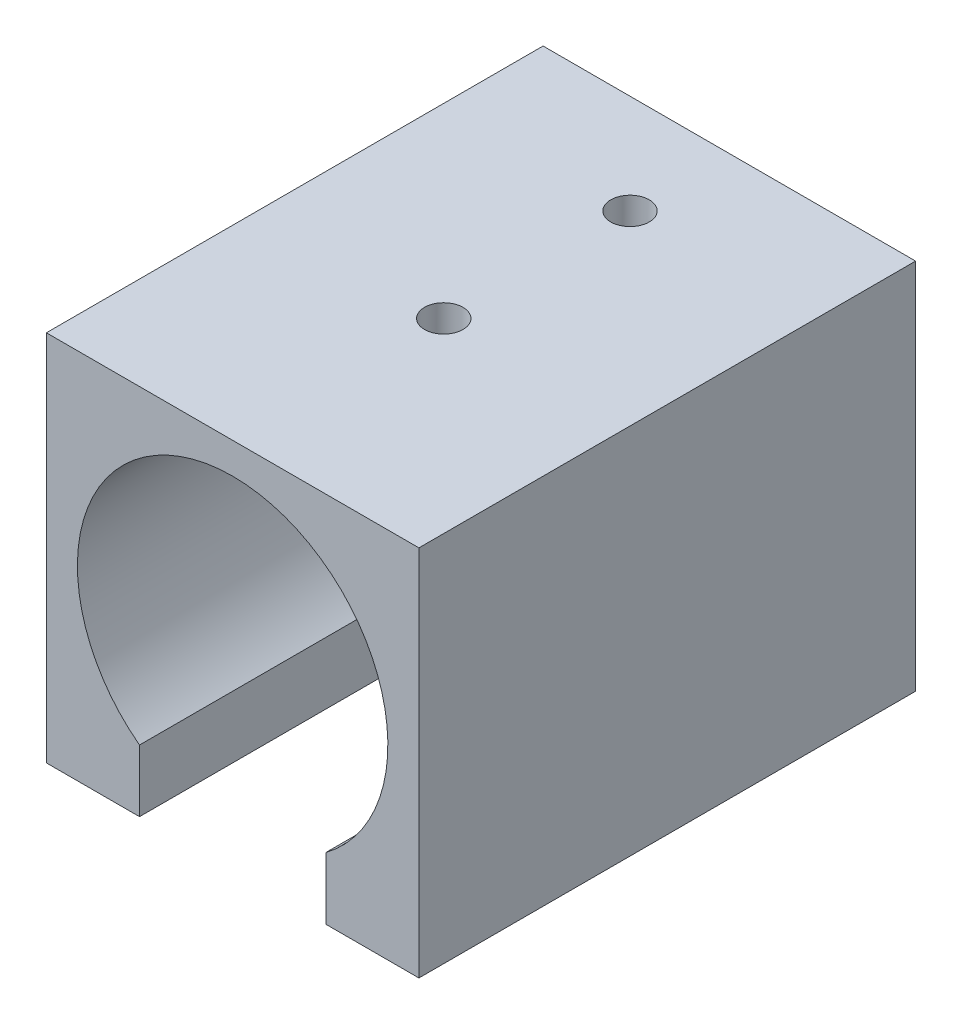
SolidWorks part; units mm, degrees
ref_plane "Front Plane" through (0, 0, 0) normal (0, 0, 1) x (1, 0, 0)
ref_plane "Top Plane" through (0, 0, 0) normal (0, 1, 0) x (1, 0, 0)
ref_plane "Right Plane" through (0, 0, 0) normal (1, 0, 0) x (0, 0, -1)
sketch "Sketch1" plane through (0, 0, 0) normal (0, 0, 1) x (1, 0, 0)
  line L0 (-15, 15) -> (15, 15)
  line L1 (-15, 15) -> (-15, -15)
  line L2 (-15, -15) -> (-7.5, -15)
  line L3 (15, 15) -> (15, -15)
  line L4 (15, -15) -> (7.5, -15)
  line L5 (-7.5, -15) -> (-7.5, -10)
  line L6 (7.5, -15) -> (7.5, -10)
  arc A2 (-7.5, -10) -> (7.5, -10) centre (0, 0) cw
  dimension "D1" = 12.5
  dimension "D2" = 5
  dimension "D3" = 30
  dimension "D4" = 30
  dimension "D5" = 15
extrude "Boss-Extrude1" add sketch "Sketch1" along normal mid plane 40
sketch "Sketch2" plane through (0, 15, 0) normal (0, 1, 0) x (1, 0, 0)
  line L0 (0, -16.5) -> (0, 16.5) construction
  line L1 (15, 20) -> (-15, 20) construction
  circle A0 centre (0, 12) radius 1.55
  circle A1 centre (0, -3) radius 1.55
  point P8 (0, 0)
  dimension "D1" = 15
  dimension "D3" = 3.1
  dimension "D2" = 8
extrude "Cut-Extrude1" cut sketch "Sketch2" against normal up to surface (2.5 mm away)
equation "\"Width\"=30"
equation "\"D4@Sketch1\"=\"Width\""
equation "\"Height\"=30"
equation "\"D3@Sketch1\"=\"Height\""
equation "\"hDist\"=5"
equation "\"vDist\"=5"
equation "\"D2@Sketch1\"=\"vDist\""
equation "\"D5@Sketch1\"=\"Height\"/2"
